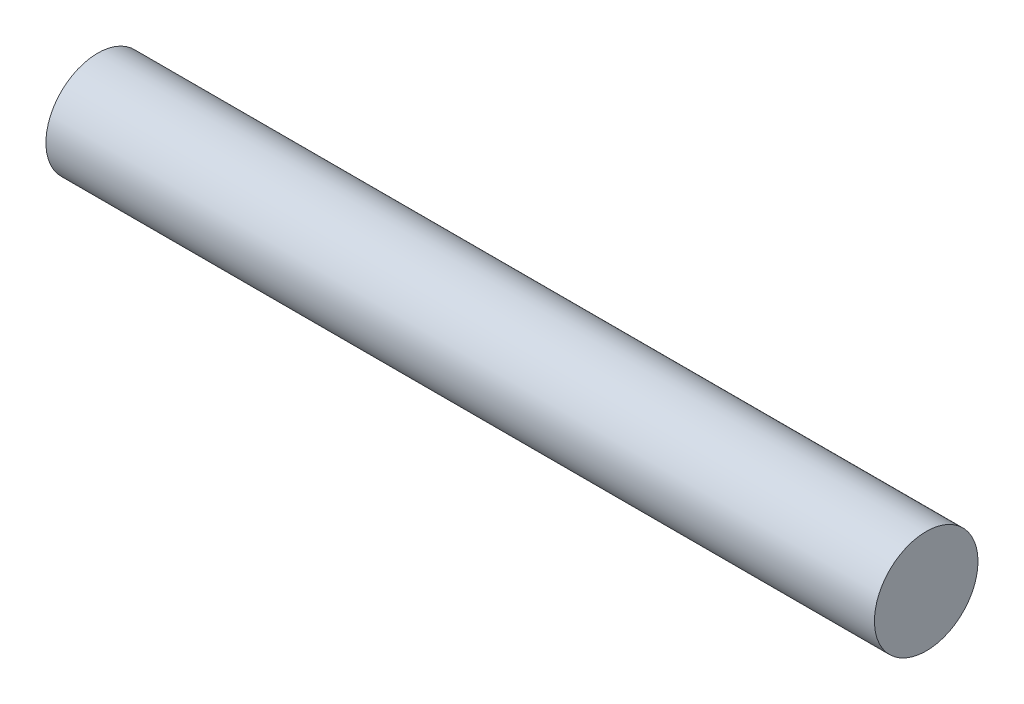
SolidWorks part; units mm, degrees
ref_plane "Front Plane" through (0, 0, 0) normal (0, 0, 1) x (1, 0, 0)
ref_plane "Top Plane" through (0, 0, 0) normal (0, 1, 0) x (1, 0, 0)
ref_plane "Right Plane" through (0, 0, 0) normal (1, 0, 0) x (0, 0, -1)
sketch "Sketch1" plane through (0, 0, 0) normal (1, 0, 0) x (0, 0, -1)
  circle A0 centre (0, 0) radius 1
  dimension "D1" = 2
extrude "Boss-Extrude1" add sketch "Sketch1" along normal blind 16
